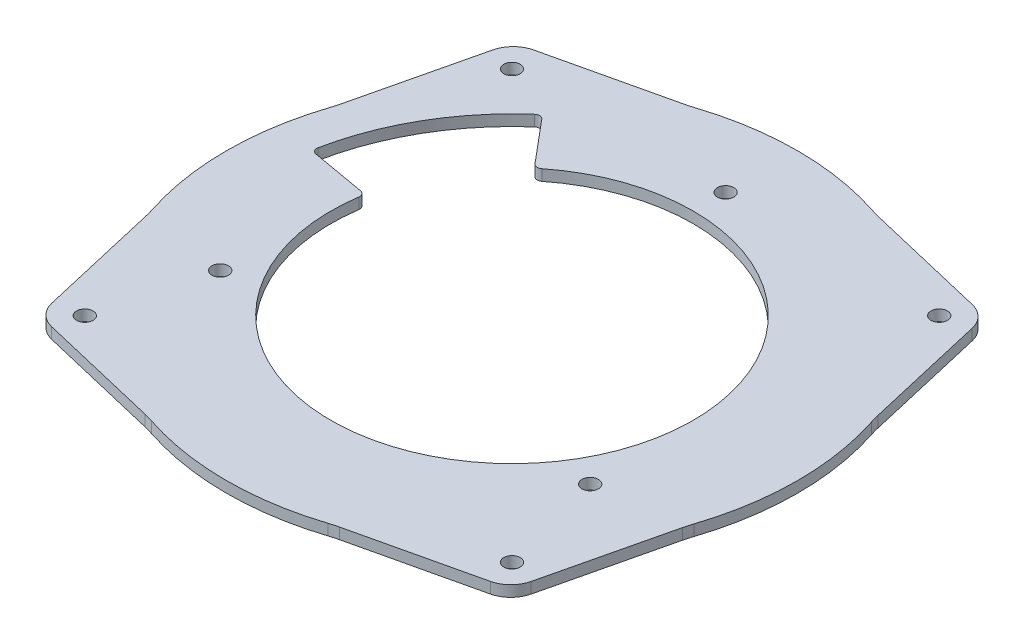
SolidWorks part; units mm, degrees
material "6061-T6 (SS)"
ref_plane "Front Plane" through (0, 0, 0) normal (0, 0, 1) x (1, 0, 0)
ref_plane "Top Plane" through (0, 0, 0) normal (0, 1, 0) x (1, 0, 0)
ref_plane "Right Plane" through (0, 0, 0) normal (1, 0, 0) x (0, 0, -1)
sketch "Sketch2" plane through (0, 0, 0) normal (0, 1, 0) x (1, 0, 0)
  line L0 (49.872, -261.8935) -> (473.872, -261.8935) construction
  line L1 (17.8971, 48.9297) -> (40.1493, 43.6512)
  line L2 (43.8664, 39.9141) -> (49.0252, 17.6338)
  line L3 (48.9297, -17.8971) -> (43.6512, -40.1493)
  line L4 (39.9141, -43.8664) -> (17.6338, -49.0252)
  line L5 (-17.8971, -48.9297) -> (-40.1493, -43.6512)
  line L6 (-43.8664, -39.9141) -> (-49.0252, -17.6338)
  line L7 (-48.9297, 17.8971) -> (-43.6512, 40.1493)
  line L8 (-39.9141, 43.8664) -> (-17.6338, 49.0252)
  line L9 (0.1397, 51.9998) -> (-0.1397, -51.9998) construction
  line L10 (-51.9998, 0.1397) -> (51.9998, -0.1397) construction
  line L11 (0, 38.8907) -> (-33.6803, -19.4454) construction
  line L12 (-38.8907, 38.8907) -> (38.8907, 38.8907) construction
  line L13 (-38.8907, 38.8907) -> (-38.8907, -38.8907) construction
  line L14 (-38.8907, -38.8907) -> (38.8907, -38.8907) construction
  line L15 (38.8907, 38.8907) -> (38.8907, -38.8907) construction
  line L16 (-33.6803, -19.4454) -> (33.6803, -19.4454) construction
  line L17 (33.6803, -19.4454) -> (0, 38.8907) construction
  line L18 (0, 38.8907) -> (0, -19.4454) construction
  line L19 (-33.6803, -19.4454) -> (16.8402, 9.7227) construction
  circle A0 centre (0, 0) radius 30 construction
  arc A3 (-17.6338, 49.0252) -> (-15.9939, 49.4792) centre (-22.1454, 68.5097) ccw
  arc A4 (0.1397, 51.9998) -> (-15.9939, 49.4792) centre (0, 0) ccw
  arc A5 (16.2596, 49.3926) -> (0.1397, 51.9998) centre (0, 0) ccw
  arc A6 (16.2596, 49.3926) -> (17.8971, 48.9297) centre (22.5132, 68.3897) ccw
  arc A7 (43.8664, 39.9141) -> (40.1493, 43.6512) centre (38.9952, 38.7862) ccw
  arc A8 (49.0252, 17.6338) -> (49.4792, 15.9939) centre (68.5097, 22.1454) ccw
  arc A9 (49.3926, -16.2596) -> (49.4792, 15.9939) centre (0, 0) ccw
  arc A10 (49.3926, -16.2596) -> (48.9297, -17.8971) centre (68.3897, -22.5132) ccw
  arc A11 (39.9141, -43.8664) -> (43.6512, -40.1493) centre (38.7862, -38.9952) ccw
  arc A12 (17.6338, -49.0252) -> (15.9939, -49.4792) centre (22.1454, -68.5097) ccw
  arc A13 (-16.2596, -49.3926) -> (15.9939, -49.4792) centre (0, 0) ccw
  arc A14 (-16.2596, -49.3926) -> (-17.8971, -48.9297) centre (-22.5132, -68.3897) ccw
  arc A15 (-43.8664, -39.9141) -> (-40.1493, -43.6512) centre (-38.9952, -38.7862) ccw
  arc A16 (-49.0252, -17.6338) -> (-49.4792, -15.9939) centre (-68.5097, -22.1454) ccw
  arc A17 (-49.3926, 16.2596) -> (-49.4792, -15.9939) centre (0, 0) ccw
  arc A18 (-49.3926, 16.2596) -> (-48.9297, 17.8971) centre (-68.3897, 22.5132) ccw
  arc A19 (-39.9141, 43.8664) -> (-43.6512, 40.1493) centre (-38.7862, 38.9952) ccw
  circle A20 centre (-38.8907, 38.8907) radius 1.5
  circle A21 centre (38.8907, 38.8907) radius 1.5
  circle A22 centre (38.8907, -38.8907) radius 1.5
  circle A23 centre (-38.8907, -38.8907) radius 1.5
  circle A27 centre (0, 0) radius 33
  circle A33 centre (0, 38.8907) radius 1.5
  circle A34 centre (-33.6803, -19.4454) radius 1.5
  circle A35 centre (33.6803, -19.4454) radius 1.5
  point P23 (0, 0)
  point P62 (0, 0)
  point P66 (0, 0)
  point P71 (0, 0)
extrude "Boss-Extrude1" add sketch "Sketch2" along normal blind 2
sketch "Sketch3" plane through (0, 2, 0) normal (0, 1, 0) x (1, 0, 0)
  line L0 (29.9159, 17.2719) -> (-29.9159, 17.2719) construction
  line L1 (-29.9159, 17.2719) -> (0, -34.5439) construction
  line L2 (0, -34.5439) -> (29.9159, 17.2719) construction
  line L3 (29.9159, 17.2719) -> (-14.9579, -8.636) construction
  line L4 (-29.9159, 17.2719) -> (14.9579, -8.636) construction
  line L5 (0, 0) -> (33, 0) construction
  line L6 (-21.212, 25.2795) -> (-28.9254, 34.472)
  line L7 (-32.4987, 5.7304) -> (-44.3163, 7.8142)
  line L8 (0, 0) -> (-29.9159, 17.2719) construction
  line L9 (-29.9159, 17.2719) -> (-38.9711, 22.5) construction
  circle A0 centre (29.9159, 17.2719) radius 1.5 construction
  circle A1 centre (-29.9159, 17.2719) radius 1.5 construction
  circle A2 centre (0, -34.5439) radius 1.5 construction
  circle A3 centre (0, 0) radius 33 construction
  arc A4 (-28.9254, 34.472) -> (-44.3163, 7.8142) centre (0, 0) ccw
  arc A5 (-21.212, 25.2795) -> (-32.4987, 5.7304) centre (0, 0) ccw
  point P6 (0, 0)
  dimension "D1" = 3
  dimension "D2" = 34.5439
  dimension "D4" = 90
  dimension "D3" = 30
  dimension "D5" = 20
  dimension "D6" = 20
extrude "Cut-Extrude1" cut sketch "Sketch3" against normal through all
fillet "Fillet1" radius 1 4 edges at (-32.4987, 1, -5.7304) (-44.3163, 1, -7.8142) (-21.212, 1, -25.2795) (-28.9254, 1, -34.472)
